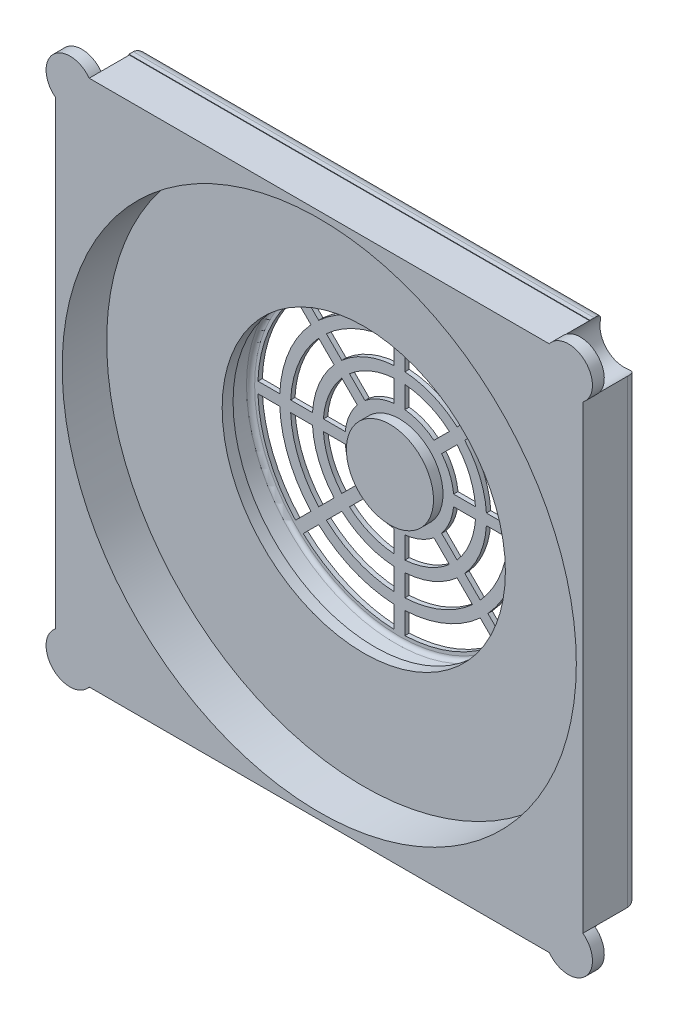
SolidWorks part; units mm, degrees
ref_plane "Front Plane" through (0, 0, 0) normal (0, 0, 1) x (1, 0, 0)
ref_plane "Top Plane" through (0, 0, 0) normal (0, 1, 0) x (1, 0, 0)
ref_plane "Right Plane" through (0, 0, 0) normal (1, 0, 0) x (0, 0, -1)
sketch "Sketch1" plane through (0, 0, 0) normal (0, 1, 0) x (1, 0, 0)
  line L0 (0, 66.7962) -> (0, -77.6353) construction
  line L1 (0, 21.5428) -> (68.2334, 21.5428)
  line L2 (70.2181, 19.7897) -> (71.6628, 8.1763)
  line L3 (71.6628, 8.1763) -> (118, 8.1763)
  line L4 (120, 6.1763) -> (120, 2.7379)
  line L5 (0, 19.5428) -> (66.4668, 19.5428)
  line L6 (68.4515, 17.7897) -> (69.8962, 6.1763)
  line L7 (69.8962, 6.1763) -> (118, 6.1763)
  line L8 (118, 6.1763) -> (118, 2.7379)
  line L9 (118, 2.7379) -> (120, 2.7379)
  line L10 (0, 19.5428) -> (0, 21.5428)
  line L11 (71.6628, 8.1763) -> (120, 8.1763) construction
  line L12 (120, 8.1763) -> (120, 2.7379) construction
  line L13 (0, 19.5428) -> (68.2334, 19.5428) construction
  line L14 (68.2334, 19.5428) -> (69.8962, 6.1763) construction
  line L15 (0, 21.5428) -> (70, 21.5428) construction
  line L16 (70, 21.5428) -> (71.6628, 8.1763) construction
  arc A0 (118, 8.1763) -> (120, 6.1763) centre (118, 6.1763) cw
  arc A1 (66.4668, 19.5428) -> (68.4515, 17.7897) centre (66.4668, 17.5428) cw
  arc A2 (68.2334, 21.5428) -> (70.2181, 19.7897) centre (68.2334, 19.5428) cw
  point P16 (120, 8.1763)
  point P23 (70, 21.5428)
  dimension "D5" = 2
  dimension "D2" = 70
  dimension "D3" = 48.3372
  dimension "D4" = 120
  dimension "D1" = 2
revolve "Revolve9" add sketch "Sketch1" angle 360 about L0
sketch "Sketch2" plane through (0, 0, -2.7379) normal (0, 0, 1) x (1, 0, 0)
  line L0 (-121, -105.5984) -> (-121, 105.5984)
  line L1 (-103.7868, -125) -> (103.7868, -125)
  line L2 (-125, -103.7868) -> (-125, 103.7868)
  line L3 (-103.7868, 125) -> (103.7868, 125)
  line L4 (125, -103.7868) -> (125, 103.7868)
  line L5 (0, 0) -> (103.7868, 103.7868) construction
  line L6 (-103.7868, 103.7868) -> (103.7868, -103.7868) construction
  line L7 (-105.5984, 121) -> (105.5984, 121)
  line L8 (121, -105.5984) -> (121, 105.5984)
  line L9 (-105.5984, -121) -> (105.5984, -121)
  arc A1 (125, 103.7868) -> (103.7868, 125) centre (114.3934, 114.3934) ccw
  arc A2 (103.7868, -125) -> (125, -103.7868) centre (114.3934, -114.3934) ccw
  arc A3 (-125, -103.7868) -> (-103.7868, -125) centre (-114.3934, -114.3934) ccw
  arc A4 (-103.7868, 125) -> (-125, 103.7868) centre (-114.3934, 114.3934) ccw
  arc A5 (-105.5984, 121) -> (-121, 105.5984) centre (-114.3934, 114.3934) ccw
  arc A6 (121, 105.5984) -> (105.5984, 121) centre (114.3934, 114.3934) ccw
  arc A7 (105.5984, -121) -> (121, -105.5984) centre (114.3934, -114.3934) ccw
  arc A8 (-121, -105.5984) -> (-105.5984, -121) centre (-114.3934, -114.3934) ccw
  circle A9 centre (0, 0) radius 118
  point P0 (0, 0)
  circle M3 centre (0, 0) radius 120
  circle M4 centre (0, 0) radius 118
  dimension "D4" = 30
  dimension "D5" = 30
  dimension "D6" = 30
  dimension "D1" = 4
  dimension "D2" = 250
extrude "Boss-Extrude8" add sketch "Sketch2" along normal blind 20 contours L0 A8 L9 A7 L8 A6 L7 A5 M3 | M4
sketch "Sketch7" plane through (0, 0, -6.1763) normal (0, 0, 1) x (1, 0, 0)
  line L1 (121, -121.2293) -> (-121, -121.2293)
  line L2 (121, -121.2293) -> (121, 121.2293)
  line L3 (121, 121.2293) -> (-121, 121.2293)
  line L4 (-121, -121.2293) -> (-121, 121.2293)
  line L5 (121, -121.2293) -> (-121, 121.2293) construction
  line L6 (121, 121.2293) -> (-121, -121.2293) construction
  point P0 (0, 0)
extrude "Boss-Extrude9" add sketch "Sketch7" against normal blind 2
sketch "Sketch8" plane through (0, 0, -6.1763) normal (0, 0, 1) x (1, 0, 0)
  circle A0 centre (0, 0) radius 67.5
  dimension "D1" = 135
extrude "Cut-Extrude7" cut sketch "Sketch8" against normal blind 2
sketch "Sketch9" plane through (0, 0, -8.1763) normal (0, 0, -1) x (-1, 0, 0)
  line L0 (-121, 121.2293) -> (121, 121.2293) construction
  line L1 (-121, -121.2293) -> (121, -121.2293)
  line L2 (-121, -121.2293) -> (-121, 121.2293)
  line L3 (-121, 121.2293) -> (121, 121.2293)
  line L4 (121, -121.2293) -> (121, 121.2293)
  line L5 (-121, -121.2293) -> (121, 121.2293) construction
  line L6 (-121, 121.2293) -> (121, -121.2293) construction
  point P0 (0, 0)
extrude "Boss-Extrude10" add sketch "Sketch9" against normal blind 7
sketch "Sketch10" plane through (0, 0, -8.1763) normal (0, 0, -1) x (-1, 0, 0)
  circle A0 centre (-114.3934, 114.3934) radius 11
  circle A1 centre (114.3934, 114.3934) radius 11
  circle A2 centre (-114.3934, -114.3934) radius 11
  circle A3 centre (114.3934, -114.3934) radius 11
extrude "Cut-Extrude8" cut sketch "Sketch10" against normal blind 20
sketch "Sketch11" plane through (0, 0, -21.5428) normal (0, 0, -1) x (-1, 0, 0)
  line L0 (0, 115.9636) -> (0, -96.8142) construction
  line L1 (-143.0602, 0) -> (195.7045, 0) construction
  line L2 (195.7045, 0) -> (0, 0) construction
  line L3 (-2.5, 2.5) -> (-169.2651, 169.2651) construction
  line L4 (-47.6957, -44.1602) -> (-40.6184, -37.0829)
  line L5 (-143.0602, 2.5) -> (-69.9553, 2.5)
  line L6 (-19.3568, 15.8213) -> (-26.4533, 22.9178)
  line L7 (-54.9432, -2.5) -> (-64.9519, -2.5)
  line L8 (-29.9967, 26.4612) -> (-37.0789, 33.5434)
  line L9 (-40.6184, 37.0829) -> (-47.6957, 44.1602)
  line L10 (-51.2337, 47.6981) -> (-171.0328, 167.4973)
  line L11 (-64.9519, 2.5) -> (-54.9432, 2.5)
  line L12 (-143.0602, 2.5) -> (195.7045, 2.5) construction
  line L13 (-49.9375, 2.5) -> (-39.9218, 2.5)
  line L14 (-34.9106, 2.5) -> (-24.8747, 2.5)
  line L15 (-19.8431, 2.5) -> (-6.0355, 2.5)
  line L16 (-6.0355, 2.5) -> (-15.799, 12.2634)
  line L17 (-2.5, 2.5) -> (195.7045, 2.5)
  line L18 (-39.9218, -2.5) -> (-49.9375, -2.5)
  line L19 (-37.0789, -33.5434) -> (-29.9967, -26.4612)
  line L20 (-26.4533, -22.9178) -> (-19.3568, -15.8213)
  line L21 (-6.0355, -2.5) -> (-19.8431, -2.5)
  line L22 (-15.799, -12.2634) -> (-6.0355, -2.5)
  line L23 (-24.8747, -2.5) -> (-34.9106, -2.5)
  line L24 (-2.5, -64.9519) -> (-2.5, -54.9432)
  line L25 (-37.0829, -40.6184) -> (-44.1602, -47.6957)
  line L26 (-26.4612, -29.9967) -> (-33.5434, -37.0789)
  line L27 (-2.5, -49.9375) -> (-2.5, -39.9218)
  line L28 (-2.5, -34.9106) -> (-2.5, -24.8747)
  line L29 (-2.5, -6.0355) -> (-12.2634, -15.799)
  line L30 (-2.5, -19.8431) -> (-2.5, -6.0355)
  line L31 (-15.8213, -19.3568) -> (-22.9178, -26.4533)
  line L32 (44.1602, -47.6957) -> (37.0829, -40.6184)
  line L33 (2.5, -54.9432) -> (2.5, -64.9519)
  line L34 (2.5, -39.9218) -> (2.5, -49.9375)
  line L35 (33.5434, -37.0789) -> (26.4612, -29.9967)
  line L36 (22.9178, -26.4533) -> (15.8213, -19.3568)
  line L37 (2.5, -6.0355) -> (2.5, -19.8431)
  line L38 (12.2634, -15.799) -> (2.5, -6.0355)
  line L39 (2.5, -24.8747) -> (2.5, -34.9106)
  line L40 (64.9519, -2.5) -> (54.9432, -2.5)
  line L41 (40.6184, -37.0829) -> (47.6957, -44.1602)
  line L42 (29.9967, -26.4612) -> (37.0789, -33.5434)
  line L43 (49.9375, -2.5) -> (39.9218, -2.5)
  line L44 (34.9106, -2.5) -> (24.8747, -2.5)
  line L45 (6.0355, -2.5) -> (15.799, -12.2634)
  line L46 (19.8431, -2.5) -> (6.0355, -2.5)
  line L47 (19.3568, -15.8213) -> (26.4533, -22.9178)
  line L48 (47.6957, 44.1602) -> (40.6184, 37.0829)
  line L51 (37.0789, 33.5434) -> (29.9967, 26.4612)
  line L52 (26.4533, 22.9178) -> (19.3568, 15.8213)
  line L54 (15.799, 12.2634) -> (6.0355, 2.5)
  line L56 (2.5, 64.9519) -> (2.5, 54.9432)
  line L57 (37.0829, 40.6184) -> (44.1602, 47.6957)
  line L58 (26.4612, 29.9967) -> (33.5434, 37.0789)
  line L59 (2.5, 49.9375) -> (2.5, 39.9218)
  line L60 (2.5, 34.9106) -> (2.5, 24.8747)
  line L61 (2.5, 6.0355) -> (12.2634, 15.799)
  line L62 (2.5, 19.8431) -> (2.5, 6.0355)
  line L63 (15.8213, 19.3568) -> (22.9178, 26.4533)
  line L64 (-44.1602, 47.6957) -> (-37.0829, 40.6184)
  line L65 (-2.5, 54.9432) -> (-2.5, 64.9519)
  line L66 (-2.5, 39.9218) -> (-2.5, 49.9375)
  line L67 (-33.5434, 37.0789) -> (-26.4612, 29.9967)
  line L68 (-22.9178, 26.4533) -> (-15.8213, 19.3568)
  line L69 (-2.5, 6.0355) -> (-2.5, 19.8431)
  line L70 (-12.2634, 15.799) -> (-2.5, 6.0355)
  line L71 (-2.5, 24.8747) -> (-2.5, 34.9106)
  line L72 (54.9432, 2.5) -> (64.9519, 2.5) [skipped]
  line L73 (39.9218, 2.5) -> (49.9375, 2.5) [skipped]
  line L74 (24.8747, 2.5) -> (34.9106, 2.5) [skipped]
  line L75 (6.0355, 2.5) -> (19.8431, 2.5) [skipped]
  arc A0 (-15.799, 12.2634) -> (-19.8431, 2.5) centre (0, 0) ccw
  arc A1 (-26.4533, 22.9178) -> (-34.9106, 2.5) centre (0, 0) ccw
  arc A2 (-37.0789, 33.5434) -> (-49.9375, 2.5) centre (0, 0) ccw
  arc A3 (-47.6957, 44.1602) -> (-64.9519, 2.5) centre (0, 0) ccw
  arc A4 (-19.3568, 15.8213) -> (-24.8747, 2.5) centre (0, 0) ccw
  arc A5 (-29.9967, 26.4612) -> (-39.9218, 2.5) centre (0, 0) ccw
  arc A6 (-40.6184, 37.0829) -> (-54.9432, 2.5) centre (0, 0) ccw
  arc A7 (-51.2337, 47.6981) -> (-69.9553, 2.5) centre (0, 0) ccw
  arc A8 (-14.1421, 14.1421) -> (-20, 0) centre (0, 0) ccw construction
  arc A9 (-17.6777, 17.6777) -> (-25, 0) centre (0, 0) ccw construction
  arc A10 (-24.7487, 24.7487) -> (-35, 0) centre (0, 0) ccw construction
  arc A11 (-28.2843, 28.2843) -> (-40, 0) centre (0, 0) ccw construction
  arc A12 (-35.3553, 35.3553) -> (-50, 0) centre (0, 0) ccw construction
  arc A13 (-38.8909, 38.8909) -> (-55, 0) centre (0, 0) ccw construction
  arc A14 (-45.9619, 45.9619) -> (-65, 0) centre (0, 0) ccw construction
  arc A15 (-49.4975, 49.4975) -> (-70, 0) centre (0, 0) ccw construction
  arc A16 (-64.9519, -2.5) -> (-47.6957, -44.1602) centre (0, 0) ccw
  arc A17 (-54.9432, -2.5) -> (-40.6184, -37.0829) centre (0, 0) ccw
  arc A18 (-49.9375, -2.5) -> (-37.0789, -33.5434) centre (0, 0) ccw
  arc A19 (-39.9218, -2.5) -> (-29.9967, -26.4612) centre (0, 0) ccw
  arc A20 (-34.9106, -2.5) -> (-26.4533, -22.9178) centre (0, 0) ccw
  arc A21 (-24.8747, -2.5) -> (-19.3568, -15.8213) centre (0, 0) ccw
  arc A22 (-19.8431, -2.5) -> (-15.799, -12.2634) centre (0, 0) ccw
  arc A23 (-44.1602, -47.6957) -> (-2.5, -64.9519) centre (0, 0) ccw
  arc A24 (-37.0829, -40.6184) -> (-2.5, -54.9432) centre (0, 0) ccw
  arc A25 (-33.5434, -37.0789) -> (-2.5, -49.9375) centre (0, 0) ccw
  arc A26 (-26.4612, -29.9967) -> (-2.5, -39.9218) centre (0, 0) ccw
  arc A27 (-22.9178, -26.4533) -> (-2.5, -34.9106) centre (0, 0) ccw
  arc A28 (-15.8213, -19.3568) -> (-2.5, -24.8747) centre (0, 0) ccw
  arc A29 (-12.2634, -15.799) -> (-2.5, -19.8431) centre (0, 0) ccw
  arc A30 (2.5, -64.9519) -> (44.1602, -47.6957) centre (0, 0) ccw
  arc A31 (2.5, -54.9432) -> (37.0829, -40.6184) centre (0, 0) ccw
  arc A32 (2.5, -49.9375) -> (33.5434, -37.0789) centre (0, 0) ccw
  arc A33 (2.5, -39.9218) -> (26.4612, -29.9967) centre (0, 0) ccw
  arc A34 (2.5, -34.9106) -> (22.9178, -26.4533) centre (0, 0) ccw
  arc A35 (2.5, -24.8747) -> (15.8213, -19.3568) centre (0, 0) ccw
  arc A36 (2.5, -19.8431) -> (12.2634, -15.799) centre (0, 0) ccw
  arc A37 (47.6957, -44.1602) -> (64.9519, -2.5) centre (0, 0) ccw
  arc A38 (40.6184, -37.0829) -> (54.9432, -2.5) centre (0, 0) ccw
  arc A39 (37.0789, -33.5434) -> (49.9375, -2.5) centre (0, 0) ccw
  arc A40 (29.9967, -26.4612) -> (39.9218, -2.5) centre (0, 0) ccw
  arc A41 (26.4533, -22.9178) -> (34.9106, -2.5) centre (0, 0) ccw
  arc A42 (19.3568, -15.8213) -> (24.8747, -2.5) centre (0, 0) ccw
  arc A43 (15.799, -12.2634) -> (19.8431, -2.5) centre (0, 0) ccw
  arc A44 (64.9519, 2.5) -> (47.6957, 44.1602) centre (0, 0) ccw
  arc A45 (54.9432, 2.5) -> (40.6184, 37.0829) centre (0, 0) ccw
  arc A46 (49.9375, 2.5) -> (37.0789, 33.5434) centre (0, 0) ccw
  arc A47 (39.9218, 2.5) -> (29.9967, 26.4612) centre (0, 0) ccw
  arc A48 (34.9106, 2.5) -> (26.4533, 22.9178) centre (0, 0) ccw
  arc A49 (24.8747, 2.5) -> (19.3568, 15.8213) centre (0, 0) ccw
  arc A50 (19.8431, 2.5) -> (15.799, 12.2634) centre (0, 0) ccw
  arc A51 (44.1602, 47.6957) -> (2.5, 64.9519) centre (0, 0) ccw
  arc A52 (37.0829, 40.6184) -> (2.5, 54.9432) centre (0, 0) ccw
  arc A53 (33.5434, 37.0789) -> (2.5, 49.9375) centre (0, 0) ccw
  arc A54 (26.4612, 29.9967) -> (2.5, 39.9218) centre (0, 0) ccw
  arc A55 (22.9178, 26.4533) -> (2.5, 34.9106) centre (0, 0) ccw
  arc A56 (15.8213, 19.3568) -> (2.5, 24.8747) centre (0, 0) ccw
  arc A57 (12.2634, 15.799) -> (2.5, 19.8431) centre (0, 0) ccw
  arc A58 (-2.5, 64.9519) -> (-44.1602, 47.6957) centre (0, 0) ccw
  arc A59 (-2.5, 54.9432) -> (-37.0829, 40.6184) centre (0, 0) ccw
  arc A60 (-2.5, 49.9375) -> (-33.5434, 37.0789) centre (0, 0) ccw
  arc A61 (-2.5, 39.9218) -> (-26.4612, 29.9967) centre (0, 0) ccw
  arc A62 (-2.5, 34.9106) -> (-22.9178, 26.4533) centre (0, 0) ccw
  arc A63 (-2.5, 24.8747) -> (-15.8213, 19.3568) centre (0, 0) ccw
  arc A64 (-2.5, 19.8431) -> (-12.2634, 15.799) centre (0, 0) ccw
  point P156 (0, 0)
  dimension "D1" = 20
  dimension "D2" = 35
  dimension "D3" = 50
  dimension "D4" = 65
  dimension "D5" = 5
  dimension "D6" = 8
  dimension "D7" = 2.5
extrude "Cut-Extrude10" cut sketch "Sketch11" against normal blind 69 contours A6 L9 A3 L11 | A5 L8 A2 L13 | A59 L65 A58 L64 | A61 L66 A60 L67 | A63 L71 A62 L68 | A4 L6 A1 L14 | A21 L23 A20 L20 | A17 L7 A16 L4 | A24 L25 A23 L24 | A28 L31 A27 L28 | L29 A29 L30 | A31 L33 A30 L32 | A33 L34 A32 L35 | A35 L39 A34 L36 | L37 A36 L38 | A42 L47 A41 L44 | A40 L42 A39 L43 | A38 L41 A37 L40 | L17 A50 L54 | A49 L17 A48 L52 | A47 L17 A46 L51 | L61 A57 L62 | A56 L63 A55 L60 | A54 L58 A53 L59 | A52 L57 A51 L56 | A45 L17 A44 L48 | A18 L19 A19 L18 | A26 L27 A25 L26 | A43 L46 L45
sketch "Sketch13" plane through (0, 0, -1.1763) normal (0, 0, 1) x (1, 0, 0)
  circle A0 centre (0, 0) radius 20
extrude "Boss-Extrude12" add sketch "Sketch13" against normal blind 21
sketch "Sketch14" plane through (0, 0, -1.1763) normal (0, 0, 1) x (1, 0, 0)
  circle A0 centre (0, 0) radius 118
extrude "Cut-Extrude11" cut sketch "Sketch14" against normal blind 2
sketch "Sketch15" plane through (0, 0, -3.1763) normal (0, 0, 1) x (1, 0, 0)
  circle A0 centre (0, 0) radius 65
extrude "Cut-Extrude12" cut sketch "Sketch15" against normal blind 12
fillet "Fillet1" radius 5 4 edges at (121, 0, -8.1763) (-121, 0, -8.1763) (0, -121.2293, -8.1763) (0, 121.2293, -8.1763)
